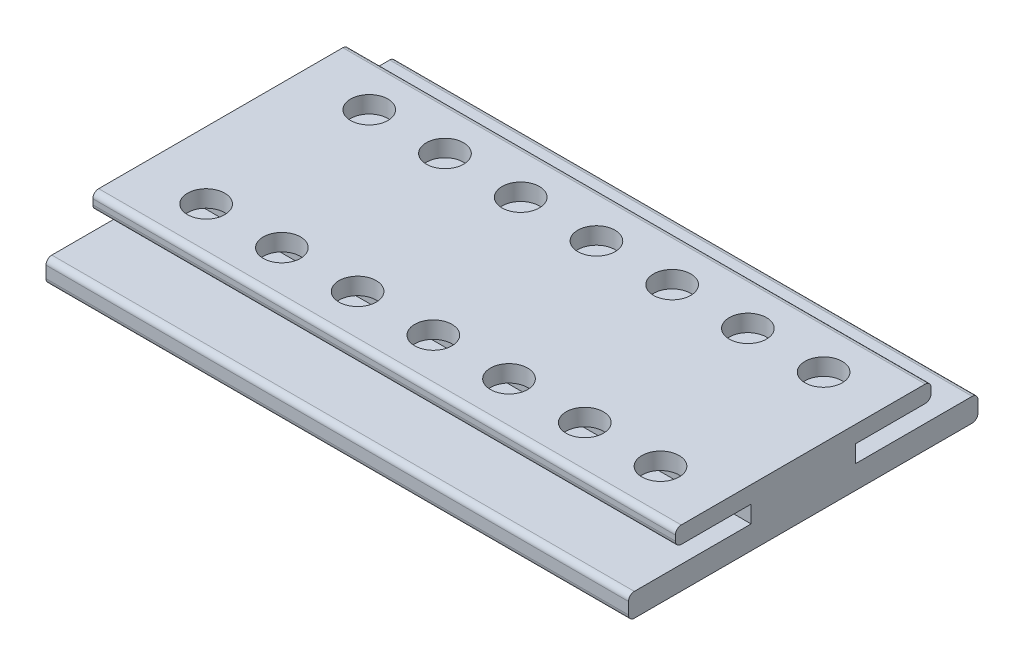
SolidWorks part; units mm, degrees
ref_plane "前视基准面" through (0, 0, 0) normal (0, 0, 1) x (1, 0, 0)
ref_plane "上视基准面" through (0, 0, 0) normal (0, 1, 0) x (1, 0, 0)
ref_plane "右视基准面" through (0, 0, 0) normal (1, 0, 0) x (0, 0, -1)
other "Configuration Table"
sketch "草图2" plane through (0, 0, 0) normal (1, 0, 0) x (0, 0, -1)
  line L0 (0, 0) -> (0, -6.4) construction
  line L1 (-20.95, -1.45) -> (-8.95, -1.45)
  line L2 (-21.95, -0.45) -> (-21.95, 0.45)
  line L3 (-20.95, 1.45) -> (20.95, 1.45)
  line L4 (21.95, -0.45) -> (21.95, 0.45)
  line L5 (-21.95, -1.45) -> (21.95, 1.45) construction
  line L6 (-21.95, 1.45) -> (21.95, -1.45) construction
  line L7 (8.95, -1.45) -> (20.95, -1.45)
  line L9 (-8.95, -4.4) -> (-8.95, -1.45)
  line L11 (8.95, -4.4) -> (8.95, -1.45)
  line L14 (-29, -8.4) -> (29, -8.4)
  line L15 (-30, -7.4) -> (-30, -5.4)
  line L16 (-29, -4.4) -> (-8.95, -4.4)
  line L17 (30, -7.4) -> (30, -5.4)
  line L18 (-30, -8.4) -> (-29.3016, -8.3534) construction
  line L19 (-30, -4.4) -> (-29.3016, -4.4466) construction
  line L20 (8.95, -4.4) -> (29, -4.4)
  line L21 (29.3016, -8.3534) -> (30, -8.4) construction
  line L22 (29.3016, -4.4466) -> (30, -4.4) construction
  line L23 (0, -8.4) -> (0, -12.8) construction
  arc A0 (-29, -8.4) -> (-30, -7.4) centre (-29, -7.4) cw
  arc A1 (29, -8.4) -> (30, -7.4) centre (29, -7.4) ccw
  arc A2 (29, -4.4) -> (30, -5.4) centre (29, -5.4) cw
  arc A3 (20.95, -1.45) -> (21.95, -0.45) centre (20.95, -0.45) ccw
  arc A4 (20.95, 1.45) -> (21.95, 0.45) centre (20.95, 0.45) cw
  arc A5 (-21.95, 0.45) -> (-20.95, 1.45) centre (-20.95, 0.45) cw
  arc A6 (-20.95, -1.45) -> (-21.95, -0.45) centre (-20.95, -0.45) cw
  arc A7 (-30, -5.4) -> (-29, -4.4) centre (-29, -5.4) cw
  point P0 (0, 0)
  point P8 (0, -2.925)
  point P13 (0, -6.4)
  dimension "D7" = 1
  dimension "D1" = 43.9
  dimension "D2" = 2.9
  dimension "D3" = 17.9
  dimension "D5" = 60
  dimension "D6" = 4
extrude "凸台-拉伸1" add sketch "草图2" along normal blind 100
sketch "草图3" plane through (0, 1.45, 0) normal (0, 1, 0) x (1, 0, 0)
  line L0 (0, 0) -> (82.1965, 0) construction
  circle A0 centre (11.493, 14) radius 3.2
  circle A1 centre (24.493, 14) radius 3.2
  circle A2 centre (37.493, 14) radius 3.2
  circle A3 centre (50.493, 14) radius 3.2
  circle A4 centre (63.493, 14) radius 3.2
  circle A5 centre (76.493, 14) radius 3.2
  circle A6 centre (89.493, 14) radius 3.2
  circle A7 centre (89.493, -14) radius 3.2
  circle A8 centre (76.493, -14) radius 3.2
  circle A9 centre (63.493, -14) radius 3.2
  circle A10 centre (50.493, -14) radius 3.2
  circle A11 centre (37.493, -14) radius 3.2
  circle A12 centre (24.493, -14) radius 3.2
  circle A13 centre (11.493, -14) radius 3.2
  dimension "D1" = 14
  dimension "D2" = 7
extrude "切除-拉伸1" cut sketch "草图3" against normal blind 8
sketch "草图4" plane through (0, -8.4, 0) normal (0, -1, 0) x (1, 0, 0)
  line L0 (0, 0) -> (74.1474, 0) construction
  line L1 (0, 29) -> (0, -29) construction
  circle A0 centre (11.9, 12.7) radius 3.18
  circle A1 centre (37.3, 12.7) radius 3.18
  circle A2 centre (62.7, 12.7) radius 3.18
  circle A3 centre (88.1, 12.7) radius 3.18
  circle A4 centre (62.7, -12.7) radius 3.18
  circle A5 centre (37.3, -12.7) radius 3.18
  circle A6 centre (11.9, -12.7) radius 3.18
  circle A7 centre (88.1, -12.7) radius 3.18
  dimension "D1" = 12.7
  dimension "D2" = 11.9
  dimension "D3" = 4
extrude "凸台-拉伸2" add sketch "草图4" along normal blind 5.1
